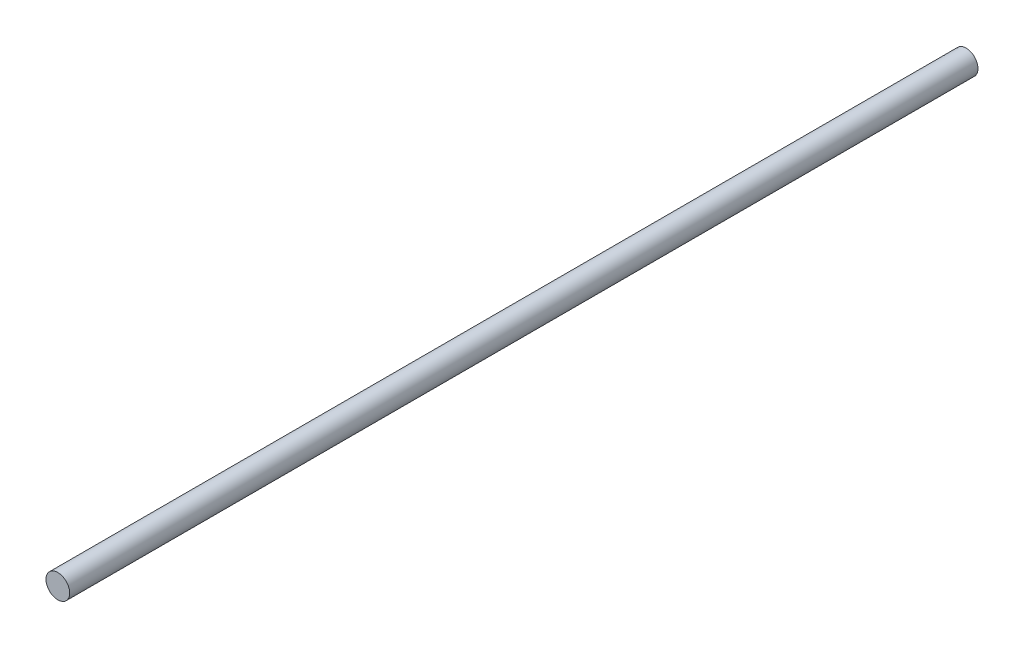
SolidWorks part; units mm, degrees
ref_plane "Спереди" through (0, 0, 0) normal (0, 0, 1) x (1, 0, 0)
ref_plane "Сверху" through (0, 0, 0) normal (0, 1, 0) x (1, 0, 0)
ref_plane "Справа" through (0, 0, 0) normal (1, 0, 0) x (0, 0, -1)
sketch "Эскиз1" plane through (0, 0, 0) normal (0, 0, 1) x (1, 0, 0)
  circle A0 centre (0, 0) radius 6
  dimension "D1" = 12
extrude "Бобышка-Вытянуть1" add sketch "Эскиз1" along normal blind 460
